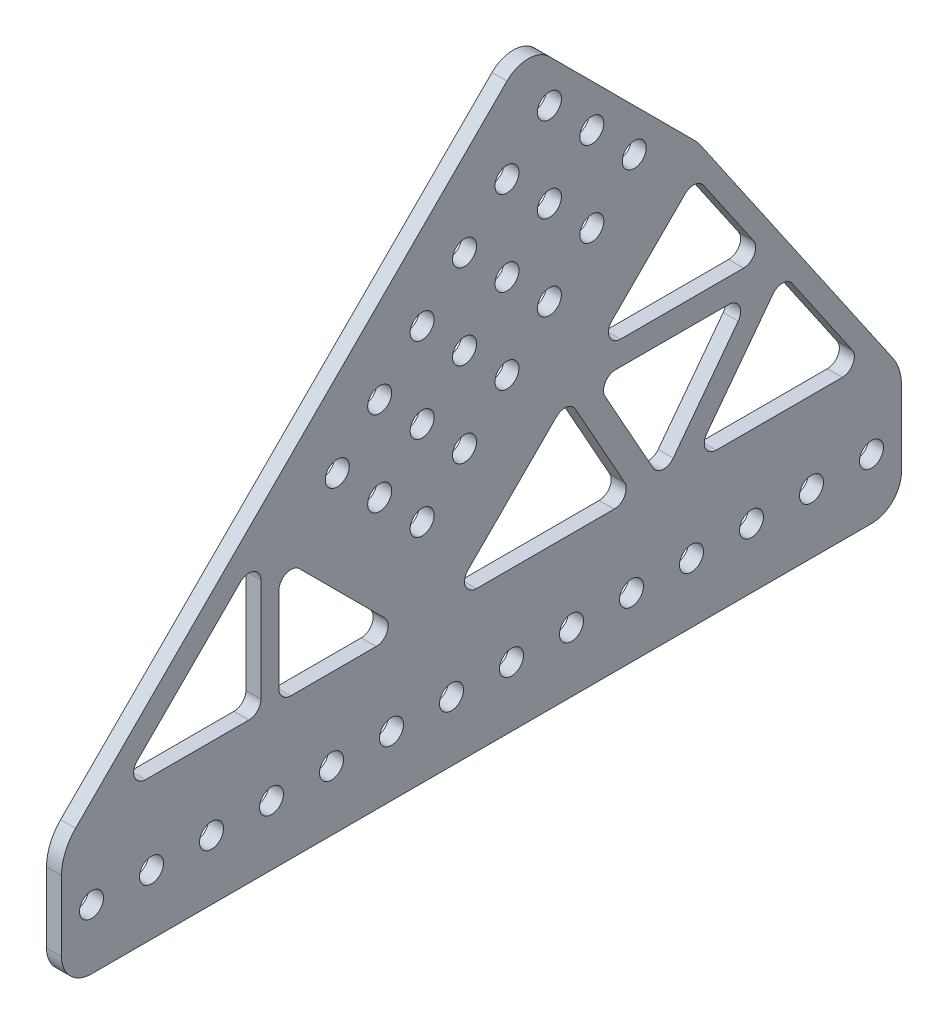
SolidWorks part; units mm, degrees
ref_plane "Front Plane" through (0, 0, 0) normal (0, 0, 1) x (1, 0, 0)
ref_plane "Top Plane" through (0, 0, 0) normal (0, 1, 0) x (1, 0, 0)
ref_plane "Right Plane" through (0, 0, 0) normal (1, 0, 0) x (0, 0, -1)
sketch "Sketch5" plane through (0, 0, 0) normal (1, 0, 0) x (0, 0, -1)
  line L0 (0, 50.8) -> (0, -76.2)
  line L1 (0, 0) -> (762, 0)
  line L2 (0, 0) -> (0, 50.8)
  line L3 (0, 50.8) -> (762, 50.8)
  line L4 (762, 0) -> (762, 50.8)
  line L5 (0, 50.8) -> (-82.55, 50.8)
  line L6 (-82.55, 50.8) -> (-82.55, -76.2)
  line L7 (-82.55, -76.2) -> (0, -76.2)
  line L8 (381, 0) -> (381, 192.0216) construction
  line L9 (762, 50.8) -> (762, -76.2)
  line L10 (844.55, 50.8) -> (844.55, -76.2)
  line L11 (762, 50.8) -> (844.55, 50.8)
  line L12 (844.55, -76.2) -> (762, -76.2)
  line L13 (-278.3903, -101.6) -> (1396.3209, -101.6) construction
  line L14 (82.55, 95.25) -> (381, 393.7)
  line L15 (917.6226, 157.1293) -> (1197.0226, 157.1293)
  line L16 (917.6226, 157.1293) -> (917.6226, -96.8707)
  line L17 (917.6226, -96.8707) -> (1197.0226, -96.8707)
  line L18 (1197.0226, 157.1293) -> (1197.0226, -96.8707)
  line L19 (0, 95.25) -> (762, 95.25)
  line L20 (0, 95.25) -> (0, 69.85)
  line L21 (0, 69.85) -> (762, 69.85)
  line L22 (762, 95.25) -> (762, 69.85)
  line L23 (381, 393.7) -> (679.45, 95.25)
  line L24 (381, 323.85) -> (791.5688, 122.6905)
  line L26 (802.1362, 159.2957) -> (1070.5742, 81.8014)
  line L27 (1070.5742, 81.8014) -> (1049.4394, 8.591)
  line L28 (1049.4394, 8.591) -> (781.0013, 86.0853)
  line L30 (781.0013, 86.0853) -> (802.1362, 159.2957)
  line L31 (-1447.8, 374.65) -> (-177.8, 374.65)
  line L32 (-177.8, 374.65) -> (-177.8, -101.6)
  line L33 (-1447.8, 374.65) -> (-1447.8, -101.6)
  line L34 (863.1448, 141.6834) -> (842.01, 68.473)
  line L35 (381, 323.85) -> (392.1755, 346.6594)
  line L36 (349.25, 361.95) -> (412.75, 361.95)
  line L37 (392.1755, 346.6594) -> (802.7443, 145.4999)
  line L38 (802.7443, 145.4999) -> (791.5688, 122.6905)
  line L39 (791.5688, 122.6905) -> (780.161, 99.9949)
  line L40 (780.161, 99.9949) -> (369.8245, 301.0406)
  line L41 (369.8245, 301.0406) -> (381, 323.85)
  circle A0 centre (50.8, -50.8) radius 50.8
  circle A1 centre (711.2, -50.8) radius 50.8
  circle A2 centre (381, 323.85) radius 12.7
  circle A3 centre (381, 323.85) radius 85.09
  point P38 (791.5688, 122.6905)
  dimension "D3" = 101.6
  dimension "D4" = 101.6
  dimension "D11" = 25.4
  dimension "D24" = 170.18
  dimension "D1" = 50.8
  dimension "D2" = 762
  dimension "D5" = 127
  dimension "D6" = 82.55
  dimension "D7" = 279.4
  dimension "D8" = 254
  dimension "D9" = 25.4
  dimension "D10" = 19.05
  dimension "D12" = 76.2
  dimension "D13" = 63.5
  dimension "D14" = 279.4
  dimension "D15" = 457.2
  dimension "D16" = 228.6
  dimension "D17" = 476.25
  dimension "D18" = 1270
  dimension "D19" = 558.8
  dimension "D20" = 80
  dimension "D21" = 63.5
  dimension "D22" = 45
  dimension "D23" = 38.1
  dimension "D25" = 25.4
  dimension "D26" = 25.4
sketch "Sketch6" plane through (0, 0, 0) normal (1, 0, 0) x (0, 0, -1)
  line L0 (762, 95.25) -> (762, 69.85) construction
  line L1 (0, 95.25) -> (762, 95.25) construction
  line L2 (0, 95.25) -> (0, 69.85) construction
  line L3 (0, 69.85) -> (762, 69.85) construction
  line L4 (762, 95.25) -> (762, 69.85)
  line L5 (0, 95.25) -> (762, 95.25)
  line L6 (0, 95.25) -> (0, 69.85)
  line L7 (0, 69.85) -> (762, 69.85)
  line L8 (349.25, 361.95) -> (412.75, 361.95) construction
  line L9 (381, 393.7) -> (679.45, 95.25) construction
  line L10 (82.55, 95.25) -> (381, 393.7) construction
  line L11 (349.25, 361.95) -> (412.75, 361.95)
  line L12 (381, 393.7) -> (679.45, 95.25)
  line L13 (82.55, 95.25) -> (381, 393.7)
  line L14 (317.5, 349.25) -> (317.5, 298.45)
  line L15 (317.5, 298.45) -> (838.2, 298.45)
  line L16 (838.2, 298.45) -> (838.2, 349.25)
  line L17 (838.2, 349.25) -> (317.5, 349.25)
  line L18 (154.392, 95.25) -> (344.892, 285.75)
  line L19 (344.892, 285.75) -> (417.108, 285.75)
  line L20 (417.108, 285.75) -> (607.608, 95.25)
  line L21 (381, -200000) -> (381, 200192.0216) construction
  line L22 (317.5, 69.85) -> (444.5, 69.85)
  line L23 (317.5, 69.85) -> (317.5, 171.45)
  line L24 (317.5, 171.45) -> (444.5, 171.45)
  line L25 (444.5, 69.85) -> (444.5, 171.45)
  circle A0 centre (381, 323.85) radius 12.7 construction
  circle A1 centre (381, 323.85) radius 12.7
  circle A2 centre (381, 323.85) radius 85.09 construction
  circle A3 centre (381, 323.85) radius 85.09
  text T0 "gearbox area"
  text T1 "sprocket"
  point P30 (381, 171.45)
  dimension "D1" = 50.8
  dimension "D2" = 25.4
  dimension "D3" = 520.7
  dimension "D4" = 63.5
  dimension "D5" = 50.8
  dimension "D6" = 50.8
  dimension "D7" = 76.2
  dimension "D8" = 101.6
  dimension "D9" = 127
sketch "tubes" plane through (0, 0, 0) normal (1, 0, 0) x (0, 0, -1)
  line L0 (158.8822, 99.7401) -> (122.9612, 135.6612)
  line L1 (0, 95.25) -> (762, 95.25)
  line L2 (0, 95.25) -> (0, 69.85)
  line L3 (0, 69.85) -> (762, 69.85)
  line L4 (762, 95.25) -> (762, 69.85)
  line L5 (158.8822, 99.7401) -> (351.9577, 292.8156)
  line L6 (351.9577, 292.8156) -> (316.0367, 328.7367)
  line L7 (316.0367, 328.7367) -> (122.9612, 135.6612)
  line L8 (82.55, 95.25) -> (381, 393.7) construction
  line L9 (154.392, 95.25) -> (344.892, 285.75) construction
  line L10 (158.8822, 99.7401) -> (154.392, 95.25) construction
  line L11 (381, -200000) -> (381, 200192.0216) construction
  line L12 (381, -200000) -> (381, 200192.0216) construction
  line L13 (603.1178, 99.7401) -> (410.0423, 292.8156)
  line L14 (410.0423, 292.8156) -> (445.9633, 328.7367)
  line L15 (445.9633, 328.7367) -> (639.0388, 135.6612)
  line L16 (603.1178, 99.7401) -> (639.0388, 135.6612)
  line L18 (12.7, 82.55) -> (25.4, 82.55) construction
  line L19 (158.8822, 117.7006) -> (167.8624, 108.7204) construction
  line L20 (158.8822, 117.7006) -> (149.9019, 108.7204) construction
  line L21 (158.8822, 117.7006) -> (149.9019, 126.6809) construction
  line L22 (158.8822, 117.7006) -> (167.8624, 126.6809) construction
  line L23 (603.1178, 117.7006) -> (594.1376, 126.6809) construction
  circle A0 centre (12.7, 82.55) radius 2.54
  circle A1 centre (25.4, 82.55) radius 2.54
  circle A2 centre (38.1, 82.55) radius 2.54
  circle A3 centre (50.8, 82.55) radius 2.54
  circle A4 centre (63.5, 82.55) radius 2.54
  circle A5 centre (76.2, 82.55) radius 2.54
  circle A6 centre (88.9, 82.55) radius 2.54
  circle A7 centre (101.6, 82.55) radius 2.54
  circle A8 centre (114.3, 82.55) radius 2.54
  circle A9 centre (127, 82.55) radius 2.54
  circle A10 centre (139.7, 82.55) radius 2.54
  circle A11 centre (152.4, 82.55) radius 2.54
  circle A12 centre (165.1, 82.55) radius 2.54
  circle A13 centre (177.8, 82.55) radius 2.54
  circle A14 centre (190.5, 82.55) radius 2.54
  circle A15 centre (203.2, 82.55) radius 2.54
  circle A16 centre (215.9, 82.55) radius 2.54
  circle A17 centre (228.6, 82.55) radius 2.54
  circle A18 centre (241.3, 82.55) radius 2.54
  circle A19 centre (254, 82.55) radius 2.54
  circle A20 centre (266.7, 82.55) radius 2.54
  circle A21 centre (279.4, 82.55) radius 2.54
  circle A22 centre (292.1, 82.55) radius 2.54
  circle A23 centre (304.8, 82.55) radius 2.54
  circle A24 centre (317.5, 82.55) radius 2.54
  circle A25 centre (330.2, 82.55) radius 2.54
  circle A26 centre (342.9, 82.55) radius 2.54
  circle A27 centre (355.6, 82.55) radius 2.54
  circle A28 centre (368.3, 82.55) radius 2.54
  circle A29 centre (381, 82.55) radius 2.54
  circle A30 centre (393.7, 82.55) radius 2.54
  circle A31 centre (406.4, 82.55) radius 2.54
  circle A32 centre (419.1, 82.55) radius 2.54
  circle A33 centre (431.8, 82.55) radius 2.54
  circle A34 centre (444.5, 82.55) radius 2.54
  circle A35 centre (457.2, 82.55) radius 2.54
  circle A36 centre (469.9, 82.55) radius 2.54
  circle A37 centre (482.6, 82.55) radius 2.54
  circle A38 centre (495.3, 82.55) radius 2.54
  circle A39 centre (508, 82.55) radius 2.54
  circle A40 centre (520.7, 82.55) radius 2.54
  circle A41 centre (533.4, 82.55) radius 2.54
  circle A42 centre (546.1, 82.55) radius 2.54
  circle A43 centre (558.8, 82.55) radius 2.54
  circle A44 centre (571.5, 82.55) radius 2.54
  circle A45 centre (584.2, 82.55) radius 2.54
  circle A46 centre (596.9, 82.55) radius 2.54
  circle A47 centre (609.6, 82.55) radius 2.54
  circle A48 centre (622.3, 82.55) radius 2.54
  circle A49 centre (635, 82.55) radius 2.54
  circle A50 centre (647.7, 82.55) radius 2.54
  circle A51 centre (660.4, 82.55) radius 2.54
  circle A52 centre (673.1, 82.55) radius 2.54
  circle A53 centre (685.8, 82.55) radius 2.54
  circle A54 centre (698.5, 82.55) radius 2.54
  circle A55 centre (711.2, 82.55) radius 2.54
  circle A56 centre (723.9, 82.55) radius 2.54
  circle A57 centre (736.6, 82.55) radius 2.54
  circle A58 centre (749.3, 82.55) radius 2.54
  circle A59 centre (762, 82.55) radius 2.54
  circle A60 centre (158.8822, 117.7006) radius 2.54
  circle A61 centre (149.9019, 126.6809) radius 2.54
  circle A62 centre (140.9217, 135.6612) radius 2.54
  circle A63 centre (167.8624, 126.6809) radius 2.54
  circle A64 centre (158.8822, 135.6612) radius 2.54
  circle A65 centre (149.9019, 144.6414) radius 2.54
  circle A66 centre (176.8427, 135.6612) radius 2.54
  circle A67 centre (167.8624, 144.6414) radius 2.54
  circle A68 centre (158.8822, 153.6217) radius 2.54
  circle A69 centre (185.8229, 144.6414) radius 2.54
  circle A70 centre (176.8427, 153.6217) radius 2.54
  circle A71 centre (167.8624, 162.6019) radius 2.54
  circle A72 centre (194.8032, 153.6217) radius 2.54
  circle A73 centre (185.8229, 162.6019) radius 2.54
  circle A74 centre (176.8427, 171.5822) radius 2.54
  circle A75 centre (203.7835, 162.6019) radius 2.54
  circle A76 centre (194.8032, 171.5822) radius 2.54
  circle A77 centre (185.8229, 180.5624) radius 2.54
  circle A78 centre (212.7637, 171.5822) radius 2.54
  circle A79 centre (203.7835, 180.5624) radius 2.54
  circle A80 centre (194.8032, 189.5427) radius 2.54
  circle A81 centre (221.744, 180.5624) radius 2.54
  circle A82 centre (212.7637, 189.5427) radius 2.54
  circle A83 centre (203.7835, 198.5229) radius 2.54
  circle A84 centre (230.7242, 189.5427) radius 2.54
  circle A85 centre (221.744, 198.5229) radius 2.54
  circle A86 centre (212.7637, 207.5032) radius 2.54
  circle A87 centre (239.7045, 198.5229) radius 2.54
  circle A88 centre (230.7242, 207.5032) radius 2.54
  circle A89 centre (221.744, 216.4835) radius 2.54
  circle A90 centre (248.6847, 207.5032) radius 2.54
  circle A91 centre (239.7045, 216.4835) radius 2.54
  circle A92 centre (230.7242, 225.4637) radius 2.54
  circle A93 centre (257.665, 216.4835) radius 2.54
  circle A94 centre (248.6847, 225.4637) radius 2.54
  circle A95 centre (239.7045, 234.444) radius 2.54
  circle A96 centre (266.6453, 225.4637) radius 2.54
  circle A97 centre (257.665, 234.444) radius 2.54
  circle A98 centre (248.6847, 243.4242) radius 2.54
  circle A99 centre (275.6255, 234.444) radius 2.54
  circle A100 centre (266.6453, 243.4242) radius 2.54
  circle A101 centre (257.665, 252.4045) radius 2.54
  circle A102 centre (284.6058, 243.4242) radius 2.54
  circle A103 centre (275.6255, 252.4045) radius 2.54
  circle A104 centre (266.6453, 261.3847) radius 2.54
  circle A105 centre (293.586, 252.4045) radius 2.54
  circle A106 centre (284.6058, 261.3847) radius 2.54
  circle A107 centre (275.6255, 270.365) radius 2.54
  circle A108 centre (302.5663, 261.3847) radius 2.54
  circle A109 centre (293.586, 270.365) radius 2.54
  circle A110 centre (284.6058, 279.3453) radius 2.54
  circle A111 centre (311.5465, 270.365) radius 2.54
  circle A112 centre (302.5663, 279.3453) radius 2.54
  circle A113 centre (293.586, 288.3255) radius 2.54
  circle A114 centre (320.5268, 279.3453) radius 2.54
  circle A115 centre (311.5465, 288.3255) radius 2.54
  circle A116 centre (302.5663, 297.3058) radius 2.54
  circle A117 centre (329.507, 288.3255) radius 2.54
  circle A118 centre (320.5268, 297.3058) radius 2.54
  circle A119 centre (311.5465, 306.286) radius 2.54
  circle A120 centre (338.4873, 297.3058) radius 2.54
  circle A121 centre (329.507, 306.286) radius 2.54
  circle A122 centre (320.5268, 315.2663) radius 2.54
  circle A123 centre (621.0783, 135.6612) radius 2.54
  circle A124 centre (612.0981, 126.6809) radius 2.54
  circle A125 centre (603.1178, 117.7006) radius 2.54
  circle A126 centre (594.1376, 126.6809) radius 2.54
  circle A127 centre (603.1178, 135.6612) radius 2.54
  circle A128 centre (612.0981, 144.6414) radius 2.54
  circle A129 centre (585.1573, 135.6612) radius 2.54
  circle A130 centre (594.1376, 144.6414) radius 2.54
  circle A131 centre (603.1178, 153.6217) radius 2.54
  circle A132 centre (576.1771, 144.6414) radius 2.54
  circle A133 centre (585.1573, 153.6217) radius 2.54
  circle A134 centre (594.1376, 162.6019) radius 2.54
  circle A135 centre (567.1968, 153.6217) radius 2.54
  circle A136 centre (576.1771, 162.6019) radius 2.54
  circle A137 centre (585.1573, 171.5822) radius 2.54
  circle A138 centre (558.2165, 162.6019) radius 2.54
  circle A139 centre (567.1968, 171.5822) radius 2.54
  circle A140 centre (576.1771, 180.5624) radius 2.54
  circle A141 centre (549.2363, 171.5822) radius 2.54
  circle A142 centre (558.2165, 180.5624) radius 2.54
  circle A143 centre (567.1968, 189.5427) radius 2.54
  circle A144 centre (540.256, 180.5624) radius 2.54
  circle A145 centre (549.2363, 189.5427) radius 2.54
  circle A146 centre (558.2165, 198.5229) radius 2.54
  circle A147 centre (531.2758, 189.5427) radius 2.54
  circle A148 centre (540.256, 198.5229) radius 2.54
  circle A149 centre (549.2363, 207.5032) radius 2.54
  circle A150 centre (522.2955, 198.5229) radius 2.54
  circle A151 centre (531.2758, 207.5032) radius 2.54
  circle A152 centre (540.256, 216.4835) radius 2.54
  circle A153 centre (513.3153, 207.5032) radius 2.54
  circle A154 centre (522.2955, 216.4835) radius 2.54
  circle A155 centre (531.2758, 225.4637) radius 2.54
  circle A156 centre (504.335, 216.4835) radius 2.54
  circle A157 centre (513.3153, 225.4637) radius 2.54
  circle A158 centre (522.2955, 234.444) radius 2.54
  circle A159 centre (495.3547, 225.4637) radius 2.54
  circle A160 centre (504.335, 234.444) radius 2.54
  circle A161 centre (513.3153, 243.4242) radius 2.54
  circle A162 centre (486.3745, 234.444) radius 2.54
  circle A163 centre (495.3547, 243.4242) radius 2.54
  circle A164 centre (504.335, 252.4045) radius 2.54
  circle A165 centre (477.3942, 243.4242) radius 2.54
  circle A166 centre (486.3745, 252.4045) radius 2.54
  circle A167 centre (495.3547, 261.3847) radius 2.54
  circle A168 centre (468.414, 252.4045) radius 2.54
  circle A169 centre (477.3942, 261.3847) radius 2.54
  circle A170 centre (486.3745, 270.365) radius 2.54
  circle A171 centre (459.4337, 261.3847) radius 2.54
  circle A172 centre (468.414, 270.365) radius 2.54
  circle A173 centre (477.3942, 279.3453) radius 2.54
  circle A174 centre (450.4535, 270.365) radius 2.54
  circle A175 centre (459.4337, 279.3453) radius 2.54
  circle A176 centre (468.414, 288.3255) radius 2.54
  circle A177 centre (441.4732, 279.3453) radius 2.54
  circle A178 centre (450.4535, 288.3255) radius 2.54
  circle A179 centre (459.4337, 297.3058) radius 2.54
  circle A180 centre (432.493, 288.3255) radius 2.54
  circle A181 centre (441.4732, 297.3058) radius 2.54
  circle A182 centre (450.4535, 306.286) radius 2.54
  circle A183 centre (423.5127, 297.3058) radius 2.54
  circle A184 centre (432.493, 306.286) radius 2.54
  circle A185 centre (441.4732, 315.2663) radius 2.54
  circle A186 centre (381, 323.85) radius 12.7 construction
  circle A187 centre (381, 323.85) radius 12.7
  dimension "D5" = 5.08
  dimension "D10" = 5.08
  dimension "D1" = 273.05
  dimension "D2" = 6.35
  dimension "D3" = 12.7
  dimension "D4" = 12.7
  dimension "D7" = 12.7
  dimension "D8" = 12.7
  dimension "D9" = 12.7
  dimension "D12" = 12.7
  dimension "D14" = 12.7
  dimension "D16" = 12.7
  dimension "D6" = 60
  dimension "D11" = 3
  dimension "D13" = 21
  dimension "D15" = 21
sketch "Sketch8" plane through (0, 0, 0) normal (1, 0, 0) x (0, 0, -1)
  line L0 (181.3328, 194.0328) -> (217.2538, 158.1118)
  line L1 (82.55, 95.25) -> (381, 393.7) construction
  line L2 (154.392, 95.25) -> (344.892, 285.75) construction
  line L3 (217.2538, 158.1118) -> (260.35, 95.25)
  line L4 (0, 95.25) -> (762, 95.25) construction
  line L5 (260.35, 95.25) -> (260.35, 69.85)
  line L6 (0, 69.85) -> (762, 69.85) construction
  line L7 (260.35, 69.85) -> (82.55, 69.85)
  line L8 (82.55, 69.85) -> (82.55, 95.25)
  line L9 (82.55, 95.25) -> (181.3328, 194.0328)
  line L10 (185.8229, 180.5624) -> (194.8032, 189.5427)
  line L11 (254, 82.55) -> (266.7, 82.55) construction
  line L12 (158.8822, 99.7401) -> (217.2538, 158.1118) construction
  line L13 (164.2703, 99.7401) -> (203.8629, 99.7401)
  line L14 (203.8629, 99.7401) -> (189.6703, 125.1401)
  line L15 (189.6703, 125.1401) -> (164.2703, 99.7401)
  line L16 (209.6822, 99.7401) -> (195.4896, 125.1401)
  line L17 (195.4896, 125.1401) -> (228.872, 125.1401)
  line L18 (228.872, 125.1401) -> (209.6822, 99.7401)
  line L19 (216.049, 99.7401) -> (252.6523, 99.7401)
  line L20 (252.6523, 99.7401) -> (235.2388, 125.1401)
  line L21 (235.2388, 125.1401) -> (216.049, 99.7401)
  line L22 (194.7503, 130.2201) -> (231.7561, 130.2201)
  line L23 (231.7561, 130.2201) -> (216.7048, 152.1746)
  line L24 (216.7048, 152.1746) -> (194.7503, 130.2201)
  line L25 (124.7572, 130.273) -> (94.2243, 99.7401)
  line L26 (94.2243, 99.7401) -> (124.7572, 99.7401)
  line L27 (124.7572, 99.7401) -> (124.7572, 130.273)
  line L28 (128.5672, 126.463) -> (128.5672, 99.7401)
  line L29 (128.5672, 99.7401) -> (155.2901, 99.7401)
  line L30 (155.2901, 99.7401) -> (128.5672, 126.463)
  line L31 (158.8822, 99.7401) -> (122.9612, 135.6612) construction
  line L32 (260.35, 95.25) -> (82.55, 95.25)
  line L33 (128.5672, 126.463) -> (124.7572, 130.273) construction
  line L34 (254, 82.55) -> (241.3, 82.55) construction
  circle A0 centre (185.8229, 144.6414) radius 2.54 construction
  circle A1 centre (167.8624, 162.6019) radius 2.54 construction
  circle A2 centre (167.8624, 144.6414) radius 2.54 construction
  circle A3 centre (158.8822, 135.6612) radius 2.54 construction
  circle A4 centre (158.8822, 153.6217) radius 2.54 construction
  circle A5 centre (149.9019, 144.6414) radius 2.54 construction
  circle A6 centre (140.9217, 135.6612) radius 2.54 construction
  circle A7 centre (149.9019, 126.6809) radius 2.54 construction
  circle A8 centre (158.8822, 117.7006) radius 2.54 construction
  circle A9 centre (167.8624, 126.6809) radius 2.54 construction
  circle A10 centre (176.8427, 135.6612) radius 2.54 construction
  circle A11 centre (176.8427, 153.6217) radius 2.54 construction
  circle A12 centre (194.8032, 153.6217) radius 2.54 construction
  circle A13 centre (203.7835, 162.6019) radius 2.54 construction
  circle A14 centre (194.8032, 171.5822) radius 2.54 construction
  circle A15 centre (185.8229, 180.5624) radius 2.54 construction
  circle A16 centre (176.8427, 171.5822) radius 2.54 construction
  circle A17 centre (185.8229, 162.6019) radius 2.54 construction
  circle A18 centre (185.8229, 144.6414) radius 2.54
  circle A19 centre (167.8624, 162.6019) radius 2.54
  circle A20 centre (167.8624, 144.6414) radius 2.54
  circle A21 centre (158.8822, 135.6612) radius 2.54
  circle A22 centre (158.8822, 153.6217) radius 2.54
  circle A23 centre (149.9019, 144.6414) radius 2.54
  circle A24 centre (140.9217, 135.6612) radius 2.54
  circle A25 centre (149.9019, 126.6809) radius 2.54
  circle A26 centre (158.8822, 117.7006) radius 2.54
  circle A27 centre (167.8624, 126.6809) radius 2.54
  circle A28 centre (176.8427, 135.6612) radius 2.54
  circle A29 centre (176.8427, 153.6217) radius 2.54
  circle A30 centre (194.8032, 153.6217) radius 2.54
  circle A31 centre (203.7835, 162.6019) radius 2.54
  circle A32 centre (194.8032, 171.5822) radius 2.54
  circle A33 centre (185.8229, 180.5624) radius 2.54
  circle A34 centre (176.8427, 171.5822) radius 2.54
  circle A35 centre (185.8229, 162.6019) radius 2.54
  circle A36 centre (254, 82.55) radius 2.54
  circle A37 centre (241.3, 82.55) radius 2.54
  circle A38 centre (228.6, 82.55) radius 2.54
  circle A39 centre (215.9, 82.55) radius 2.54
  circle A40 centre (203.2, 82.55) radius 2.54
  circle A41 centre (190.5, 82.55) radius 2.54
  circle A42 centre (177.8, 82.55) radius 2.54
  circle A43 centre (165.1, 82.55) radius 2.54
  circle A44 centre (152.4, 82.55) radius 2.54
  circle A45 centre (139.7, 82.55) radius 2.54
  circle A46 centre (127, 82.55) radius 2.54
  circle A47 centre (114.3, 82.55) radius 2.54
  circle A48 centre (101.6, 82.55) radius 2.54
  circle A49 centre (88.9, 82.55) radius 2.54
  point P6 (190.3131, 185.0526)
  point P19 (260.35, 82.55)
  point P99 (212.1808, 125.1401)
  dimension "D15" = 5.08
  dimension "D1" = 3.81
  dimension "D2" = 3.81
  dimension "D3" = 3.81
  dimension "D4" = 3.81
  dimension "D5" = 5.08
  dimension "D6" = 5.08
  dimension "D7" = 5.08
  dimension "D8" = 5.08
  dimension "D9" = 5.08
  dimension "D10" = 50.8
  dimension "D11" = 25.4
  dimension "D12" = 5.08
  dimension "D13" = 3.81
  dimension "D14" = 5.08
  dimension "D17" = 12.7
  dimension "D16" = 14
extrude "Boss-Extrude1" add sketch "Sketch8" along normal blind 3.175
fillet "Fillet1" radius 2.54 18 edges at (1.5875, 125.1401, -195.4896) (1.5875, 99.7401, -209.6822) (1.5875, 125.1401, -228.872) (1.5875, 99.7401, -164.2703) (1.5875, 99.7401, -203.8629) (1.5875, 99.7401, -216.049) (1.5875, 99.7401, -252.6523) (1.5875, 125.1401, -235.2388) (1.5875, 130.273, -124.7572) (1.5875, 99.7401, -94.2243) (1.5875, 99.7401, -124.7572) (1.5875, 126.463, -128.5672) (1.5875, 99.7401, -128.5672) (1.5875, 99.7401, -155.2901) (1.5875, 125.1401, -189.6703) (1.5875, 130.2201, -194.7503) (1.5875, 130.2201, -231.7561) (1.5875, 152.1746, -216.7048)
fillet "Fillet2" radius 6.35 3 edges at (1.5875, 69.85, -260.35) (1.5875, 69.85, -82.55) (1.5875, 194.0328, -181.3328)
fillet "Fillet3" radius 10.16 2 edges at (1.5875, 95.25, -82.55) (1.5875, 95.25, -260.35)
fillet "Fillet4" radius 12.7 1 edges at (1.5875, 158.1118, -217.2538)
